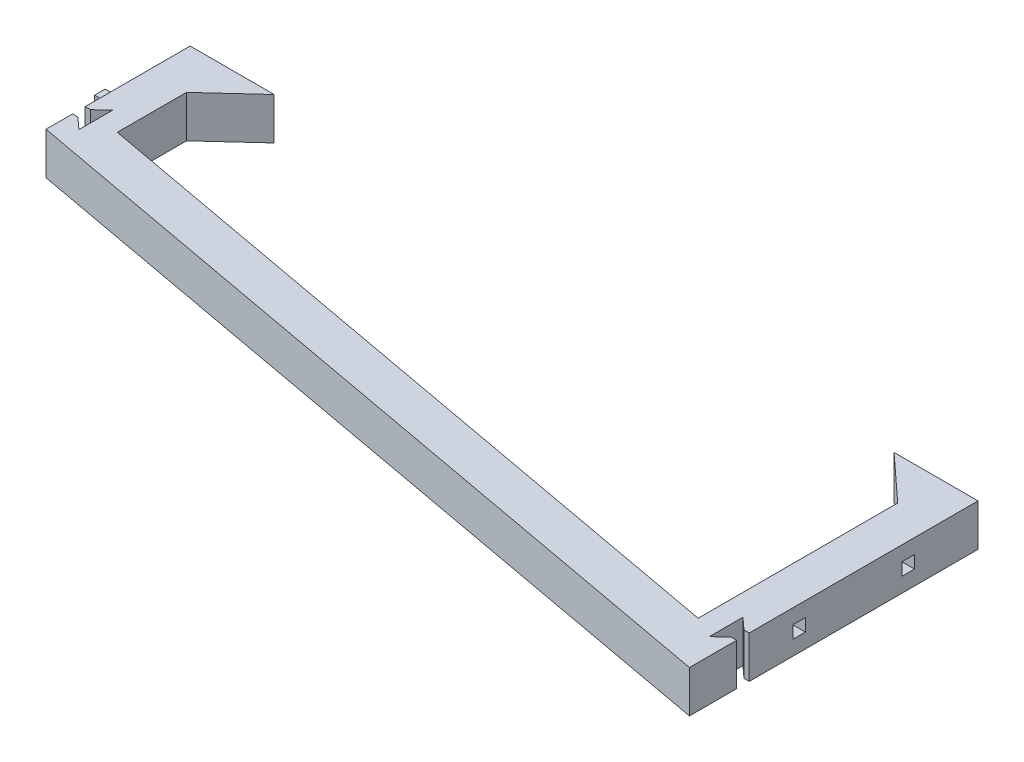
SolidWorks part; units mm, degrees
ref_plane "Přední rovina" through (0, 0, 0) normal (0, 0, 1) x (1, 0, 0)
ref_plane "Horní rovina" through (0, 0, 0) normal (0, 1, 0) x (1, 0, 0)
ref_plane "Pravá rovina" through (0, 0, 0) normal (1, 0, 0) x (0, 0, -1)
sketch "Skica1" plane through (0, 0, 0) normal (0, 1, 0) x (1, 0, 0)
  line L0 (0, 0) -> (0, -55)
  line L1 (0, -55) -> (-150.15, -27.4721)
  line L2 (-150.15, -27.4721) -> (-150.15, 0)
  line L3 (-150.15, 0) -> (-142.85, 0)
  line L4 (-142.85, 0) -> (-142.85, -21.1855)
  line L5 (-142.85, -21.1855) -> (-7.3, -46.0366)
  line L6 (-7.3, -46.0366) -> (-7.3, 0)
  line L7 (-7.3, 0) -> (0, 0)
  dimension "D1" = 55
  dimension "D2" = 7.3
  dimension "D3" = 7.3
  dimension "D4" = 150.15
  dimension "D5" = 7.5
  dimension "D6" = 27.4721
extrude "Přidat vysunutím1" add sketch "Skica1" along normal blind 8
sketch "Skica3" plane through (0, 8, 0) normal (0, 1, 0) x (1, 0, 0)
  line L12 (0, -55) -> (0, 0) construction
  line L13 (-3.2, -41.6) -> (0, -41.6)
  line L14 (-3.2, -41.6) -> (-3.2, -48)
  line L15 (-3.2, -48) -> (0, -48)
  line L16 (0, -41.6) -> (0, -48)
  line L17 (0, -43.6) -> (-1, -43.6)
  line L18 (-1, -43.6) -> (-3.2, -41.6)
  line L19 (-3.2, -48) -> (-1, -46)
  line L20 (-1, -46) -> (0, -46)
  line L21 (0, -46) -> (0, -43.6)
  dimension "D1" = 6.4
  dimension "D2" = 3.2
  dimension "D3" = 2.4
  dimension "D4" = 2
  dimension "D5" = 1
  dimension "D6" = 1
  dimension "D7" = 7
extrude "Odebrat vysunutím1" cut sketch "Skica3" against normal through all contours L19 L20 L16 L17 L18 L14
sketch "Skica6" plane through (0, 8, 0) normal (0, 1, 0) x (1, 0, 0)
  line L9 (-150.15, 0) -> (-134.15, 0)
  line L10 (-150.15, 0) -> (-150.15, -8)
  line L11 (-150.15, -8) -> (-134.15, -8)
  line L12 (-134.15, 0) -> (-134.15, -8)
  line L13 (0, 0) -> (-16, 0)
  line L14 (0, 0) -> (0, -8)
  line L19 (0, -8) -> (-16, -8)
  line L20 (-16, 0) -> (-16, -8)
  dimension "D1" = 8
  dimension "D2" = 16
  dimension "D4" = 8
  dimension "D5" = 16
extrude "Přidat vysunutím3" add sketch "Skica6" against normal blind 8 contours L20 L19 L14 L13 | L9 L12 L11 L10
sketch "Skica9" plane through (0, 0, 0) normal (0, -1, 0) x (1, 0, 0)
  line L8 (-142.85, 8) -> (-134.15, 8)
  line L9 (-134.15, 8) -> (-134.15, 0)
  line L10 (-134.15, 0) -> (-142.85, 8)
  line L11 (-16, 8) -> (-7.3, 8)
  line L12 (-7.3, 8) -> (-16, 0)
  line L13 (-16, 0) -> (-16, 8)
extrude "Odebrat vysunutím4" cut sketch "Skica9" against normal through all
sketch "Skica4" plane through (0, 0, 0) normal (1, 0, 0) x (0, 0, -1)
  line L26 (-35.3, 5.2) -> (-32.9, 5.2)
  line L27 (-35.3, 5.2) -> (-35.3, 2.8)
  line L28 (-35.3, 2.8) -> (-32.9, 2.8)
  line L29 (-32.9, 5.2) -> (-32.9, 2.8)
  line L30 (-14.5, 5.2) -> (-12.1, 5.2)
  line L31 (-14.5, 5.2) -> (-14.5, 2.8)
  line L32 (-14.5, 2.8) -> (-12.1, 2.8)
  line L33 (-12.1, 5.2) -> (-12.1, 2.8)
  line L34 (-43.6, 8) -> (0, 8) construction
  line L35 (-55, 0) -> (-46, 0) construction
  line L37 (0, 8) -> (0, 0) construction
  point P18 (-13.3, 2.8)
  dimension "D4" = 12.1
  dimension "D10" = 2.4
  dimension "D11" = 2.4
  dimension "D12" = 2.8
  dimension "D13" = 2.8
  dimension "D14" = 2.4
  dimension "D15" = 2.4
  dimension "D16" = 18.4
extrude "Odebrat vysunutím2" cut sketch "Skica4" against normal blind 4.4
sketch "Skica5" plane through (-150.15, 0, 0) normal (-1, 0, 0) x (0, 0, 1)
  line L0 (0, 8) -> (27.4721, 8) construction
  line L5 (12.2, 5) -> (14.2, 5)
  line L6 (12.2, 5) -> (12.2, 3)
  line L7 (12.2, 3) -> (14.2, 3)
  line L8 (14.2, 5) -> (14.2, 3)
  line L10 (0, 8) -> (0, 0) construction
  dimension "D1" = 12.2
  dimension "D6" = 2
  dimension "D7" = 2
  dimension "D8" = 3
extrude "Přidat vysunutím2" add sketch "Skica5" along normal blind 4
sketch "Skica10" plane through (0, 8, 0) normal (0, 1, 0) x (1, 0, 0)
  line L0 (-150.15, -22.4) -> (-149.15, -22.4)
  line L5 (-134.15, 0) -> (-150.15, 0) construction
  line L6 (-150.15, 0) -> (-150.15, -27.4721) construction
  line L7 (-150.15, -20) -> (-149.15, -20)
  line L8 (-149.15, -20) -> (-146.95, -18)
  line L9 (-146.95, -18) -> (-146.95, -24.4)
  line L10 (-146.95, -24.4) -> (-149.15, -22.4)
  line L11 (-150.15, -22.4) -> (-150.15, -20)
  dimension "D1" = 6.4
  dimension "D2" = 2.4
  dimension "D3" = 1
  dimension "D4" = 1
  dimension "D5" = 2
  dimension "D6" = 3.2
  dimension "D7" = 18
extrude "Odebrat vysunutím5" cut sketch "Skica10" against normal through all
sketch "Skica12" plane through (0, 0, 0) normal (0, 0, -1) x (-1, 0, 0)
  line L0 (0, 0) -> (16, 0) construction
  line L1 (134.15, 0) -> (150.15, 0) construction
  line L2 (150.15, 8) -> (150.15, 0) construction
  line L3 (0, 8) -> (0, 0) construction
  circle A0 centre (3.65, 4) radius 2.2
  circle A1 centre (146.5, 4) radius 2.2
  dimension "D1" = 4.4
  dimension "D2" = 4.4
  dimension "D3" = 4
  dimension "D4" = 4
  dimension "D5" = 3.65
  dimension "D6" = 3.65
extrude "Odebrat vysunutím7" cut sketch "Skica12" against normal blind 9.4
